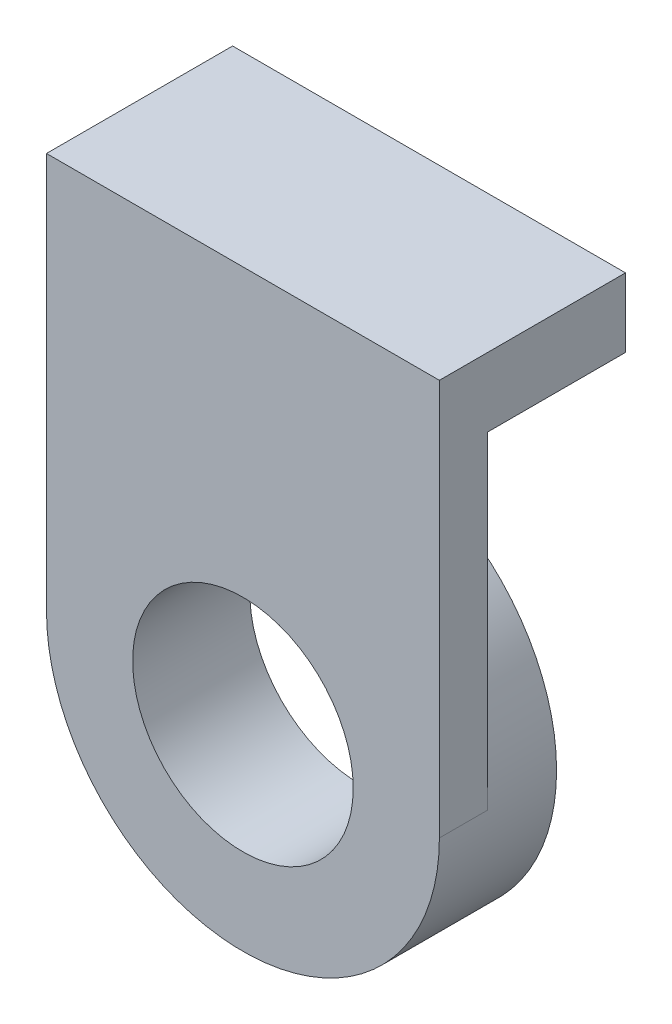
SolidWorks part; units mm, degrees
ref_plane "Płaszczyzna przednia" through (0, 0, 0) normal (0, 0, 1) x (1, 0, 0)
ref_plane "Płaszczyzna górna" through (0, 0, 0) normal (0, 1, 0) x (1, 0, 0)
ref_plane "Płaszczyzna prawa" through (0, 0, 0) normal (1, 0, 0) x (0, 0, -1)
sketch "Szkic1" plane through (0, 0, 0) normal (0, 0, 1) x (1, 0, 0)
  circle A0 centre (0, 0) radius 2.85
  circle A1 centre (0, 0) radius 1.6
  dimension "D1" = 5.7
  dimension "D2" = 3.2
extrude "Dodanie-wyciągnięcie1" add sketch "Szkic1" along normal blind 1
sketch "Szkic2" plane through (0, 0, 1) normal (0, 0, 1) x (1, 0, 0)
  line L0 (0, 0) -> (0, 5.75) construction
  line L1 (-2.85, 0) -> (-2.85, 5.75)
  line L2 (2.85, 0) -> (2.85, 5.75)
  line L3 (-2.85, 5.75) -> (2.85, 5.75)
  arc A0 (-2.85, 0) -> (2.85, 0) centre (0, 0) ccw
  arc A1 (2.85, 5.75) -> (-2.85, 5.75) centre (0, 5.75) ccw
  circle A2 centre (0, 0) radius 2.85 construction
  circle A3 centre (0, 0) radius 1.6 construction
  circle A4 centre (0, 0) radius 1.6
  point P3 (0, 2.875)
  dimension "D1" = 5.75
extrude "Dodanie-wyciągnięcie2" add sketch "Szkic2" along normal blind 0.7
sketch "Szkic3" plane through (0, 0, 1) normal (0, 0, -1) x (-1, 0, 0)
  line L0 (2.85, 0) -> (2.85, 5.75) construction
  line L1 (-2.85, 5.75) -> (2.85, 5.75)
  line L2 (-2.85, 5.75) -> (-2.85, 4.75)
  line L3 (-2.85, 4.75) -> (2.85, 4.75)
  line L4 (2.85, 5.75) -> (2.85, 4.75)
  dimension "D1" = 1
extrude "Dodanie-wyciągnięcie3" add sketch "Szkic3" along normal blind 2
